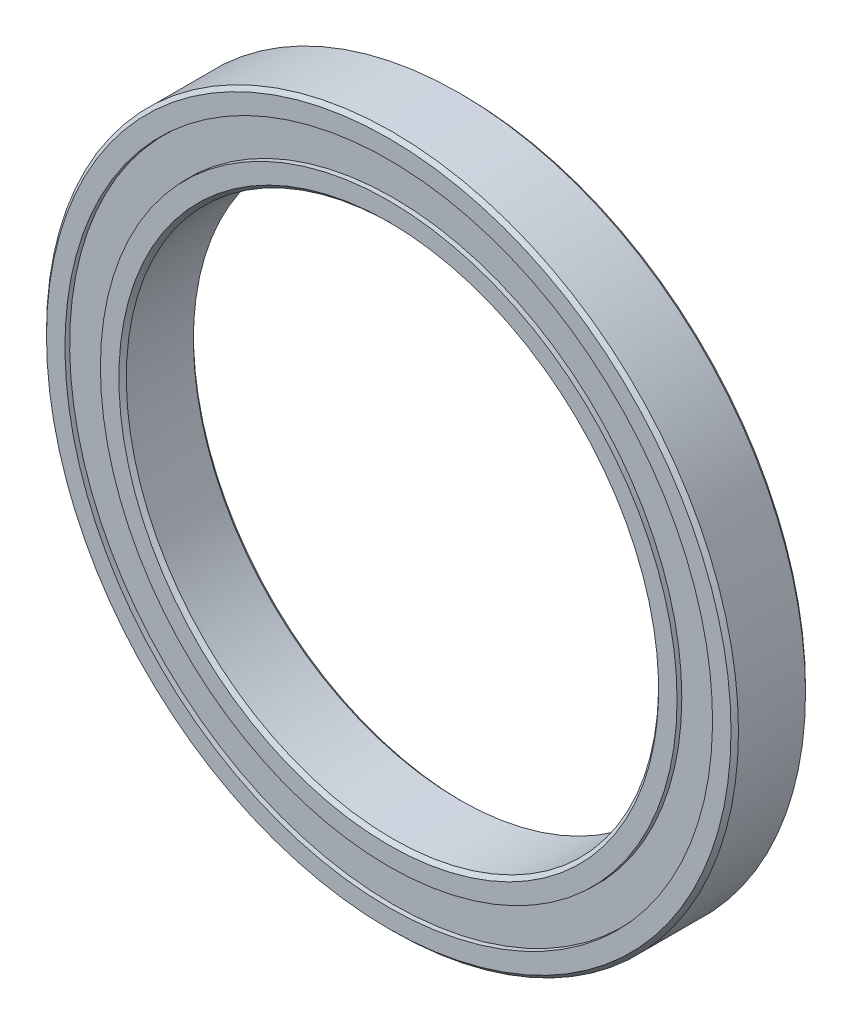
SolidWorks part; units mm, degrees
ref_plane "Front Plane" through (0, 0, 0) normal (0, 0, 1) x (1, 0, 0)
ref_plane "Top Plane" through (0, 0, 0) normal (0, 1, 0) x (1, 0, 0)
ref_plane "Right Plane" through (0, 0, 0) normal (1, 0, 0) x (0, 0, -1)
sketch "Sketch1" plane through (0, 0, 0) normal (0, 0, 1) x (1, 0, 0)
  circle A0 centre (0, 0) radius 32.5
  circle A1 centre (0, 0) radius 25
  dimension "OD" = 65
  dimension "ID" = 50
sketch "Sketch8" plane through (0, 0, 0) normal (1, 0, 0) x (0, 0, -1)
  line L1 (-3.5, 32.5) -> (3.5, 32.5)
  line L2 (-3.5, 32.5) -> (-3.5, -32.5)
  line L3 (-3.5, -32.5) -> (3.5, -32.5)
  line L4 (3.5, 32.5) -> (3.5, -32.5)
  line L5 (-3.5, 32.5) -> (3.5, -32.5) construction
  line L6 (-3.5, -32.5) -> (3.5, 32.5) construction
  point P0 (0, 0)
  point P6 (0, -32.5)
  dimension "Width" = 7
sketch "Sketch5" plane through (0, 0, 0) normal (1, 0, 0) x (0, 0, -1)
  line L0 (-3.5, 0) -> (3.5, 0) construction
  line L1 (0, 32.5) -> (0, -32.5) construction
  line L2 (3.15, 32.5) -> (-3.15, 32.5)
  line L3 (-3.15, 32.5) -> (-3.5, 32.15)
  line L4 (-3.5, 32.15) -> (-3.5, 30.4167)
  line L5 (-3.5, 30.4167) -> (-1.5556, 30.4167)
  line L6 (3.5, 30.4167) -> (1.5556, 30.4167)
  line L7 (3.5, 32.15) -> (3.5, 30.4167)
  line L8 (3.15, 32.5) -> (3.5, 32.15)
  line L9 (0, 32.5) -> (0, 28.75) construction
  line L10 (0, 28.75) -> (0, 25) construction
  line L11 (-2.2798, 28.75) -> (-3.5, 28.75) construction
  line L12 (2.6994, 27.1087) -> (3.0804, 27.1087)
  line L13 (-2.6994, 27.1087) -> (-3.0804, 27.1087)
  line L14 (-2.6994, 27.1087) -> (-2.6994, 30.3913)
  line L15 (-2.6994, 30.3913) -> (-3.0804, 30.3913)
  line L16 (-3.0804, 27.1087) -> (-3.0804, 30.3913)
  line L17 (-2.6994, 27.1087) -> (-3.0804, 30.3913) construction
  line L18 (-2.6994, 30.3913) -> (-3.0804, 27.1087) construction
  line L19 (3.0804, 27.1087) -> (3.0804, 30.3913)
  line L20 (2.6994, 30.3913) -> (3.0804, 30.3913)
  line L21 (2.6994, 27.1087) -> (2.6994, 30.3913)
  line L22 (0, 32.5) -> (0, -32.5) construction
  line L23 (3.5, 0) -> (3.5, 32.5) construction
  line L24 (3.5, 32.5) -> (3.15, 32.5) construction
  line L25 (-3.5, 0) -> (-3.5, 32.5) construction
  line L26 (-3.5, 32.5) -> (-3.15, 32.5) construction
  line L27 (3.5, 0) -> (3.5, -32.5) construction
  line L28 (-3.5, 0) -> (-3.5, -32.5) construction
  line L29 (-3.5, -32.5) -> (3.5, -32.5) construction
  arc A0 (-1.5556, 30.4167) -> (1.5556, 30.4167) centre (0, 28.75) cw
  circle A1 centre (0, 28.75) radius 2.2798 construction
  point P14 (0, 25)
  point P15 (-2.8899, 28.75)
  dimension "D1" = 45
  dimension "D2" = 0.35
  dimension "D3" = 3.1111
  dimension "D4" = 1.6667
  dimension "D5" = 0.381
  dimension "D6" = 0.0254
revolve "Revolve1" add sketch "Sketch5" angle 360 about L0
sketch "Sketch3" plane through (0, 0, 0) normal (1, 0, 0) x (0, 0, -1)
  line L0 (-3.5, 27.0833) -> (-1.5556, 27.0833)
  line L1 (0, 32.5) -> (0, -32.5) construction
  line L2 (-3.5, 32.15) -> (-3.5, 30.4167) construction
  line L3 (-3.5, 27.0833) -> (-3.5, 25.35)
  line L4 (-3.15, 32.5) -> (-3.5, 32.15) construction
  line L5 (-3.5, 25.35) -> (-3.15, 25)
  line L6 (-3.15, 25) -> (3.15, 25)
  line L7 (3.15, 32.5) -> (3.15, -32.5) construction
  line L8 (3.15, 25) -> (3.5, 25.35)
  line L9 (3.5, -32.15) -> (3.5, 32.15) construction
  line L10 (3.5, 25.35) -> (3.5, 27.0833)
  line L11 (3.5, 27.0833) -> (1.5556, 27.0833)
  line L13 (3.15, 32.5) -> (3.5, 32.15) construction
  arc A0 (1.5556, 30.4167) -> (-1.5556, 30.4167) centre (0, 28.75) ccw construction
  arc A1 (1.5556, 27.0833) -> (-1.5556, 27.0833) centre (0, 28.75) cw
revolve "Revolve3" add sketch "Sketch3" angle 360 about L0
sketch "Sketch4" plane through (0, 0, 0) normal (1, 0, 0) x (0, 0, -1)
  line L0 (-2.2798, 28.75) -> (2.2798, 28.75)
  arc A2 (-2.2798, 28.75) -> (2.2798, 28.75) centre (0, 28.75) cw
  arc A3 (1.5556, 30.4167) -> (-1.5556, 30.4167) centre (0, 28.75) ccw construction
revolve "Revolve4" add sketch "Sketch4" angle 360 about L0
pattern_circular "CirPattern1" count 23 every 15.652 about axis through (0, 0, 0) along (0, 0, 1) of bodies 104
equation "\"D2@Sketch5\" = \"Width@Sketch8\" * .05"
equation "\"D3@Sketch5\" = \"Width@Sketch8\" / 2.25"
equation "\"D4@Sketch5\"=((\"OD@Sketch1\"-\"ID@Sketch1\")/2)/4.5"
equation "\"D2@CirPattern1\" = 360/\"Balls@CirPattern1\""
